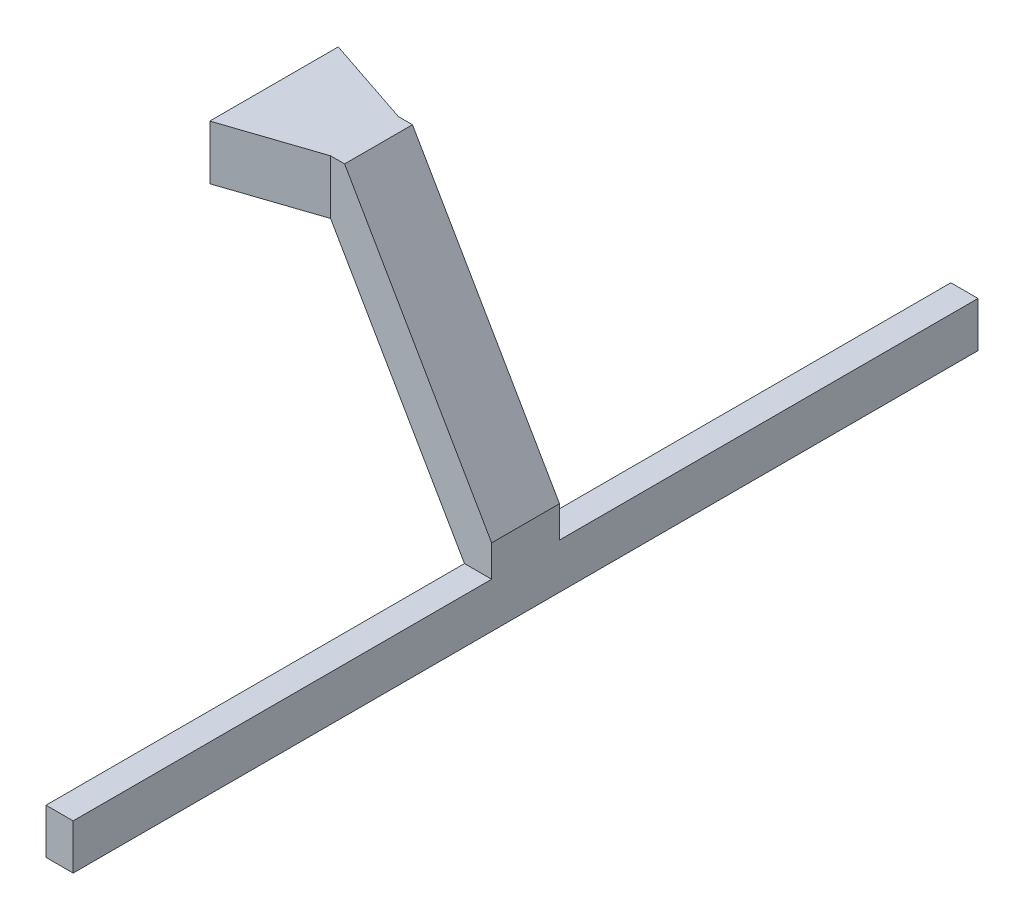
SolidWorks part; units mm, degrees
ref_plane "Plan de face" through (0, 0, 0) normal (0, 0, 1) x (1, 0, 0)
ref_plane "Plan de dessus" through (0, 0, 0) normal (0, 1, 0) x (1, 0, 0)
ref_plane "Plan de droite" through (0, 0, 0) normal (1, 0, 0) x (0, 0, -1)
sketch "Esquisse1" plane through (0, 0, 0) normal (0, 0, 1) x (1, 0, 0)
  line L0 (-29.9025, 15.2237) -> (-6.8025, 15.2237)
  line L1 (-6.8025, 15.2237) -> (25.6975, -41.0679)
  line L4 (19.6975, -58.0333) -> (19.6975, -48.0333)
  line L5 (19.6975, -48.0333) -> (-9.8958, 3.2237)
  line L6 (-9.8958, 3.2237) -> (-29.9025, 3.2237)
  line L7 (-29.9025, 3.2237) -> (-29.9025, 15.2237)
  line L8 (25.6975, -41.0679) -> (25.6975, -58.0333)
  line L9 (25.6975, -58.0333) -> (19.6975, -58.0333)
  dimension "D1" = 23.1
  dimension "D2" = 12
  dimension "D3" = 6
  dimension "D4" = 120
  dimension "D5" = 65
  dimension "D6" = 10
extrude "Boss.-Extru.1" add sketch "Esquisse1" along normal blind 15
sketch "Esquisse5" plane through (25.6975, 0, 0) normal (1, 0, 0) x (0, 0, -1)
  line L0 (-15, -58.0333) -> (0, -58.0333) construction
  line L1 (-107.5, -48.0333) -> (92.5, -48.0333)
  line L2 (-107.5, -48.0333) -> (-107.5, -58.0333)
  line L3 (-107.5, -58.0333) -> (92.5, -58.0333)
  line L4 (92.5, -48.0333) -> (92.5, -58.0333)
  line L6 (0, -58.0333) -> (0, -41.0679) construction
  line L7 (-15, -58.0333) -> (-15, -41.0679) construction
  dimension "D1" = 0
  dimension "D2" = 10
  dimension "D3" = 92.5
  dimension "D4" = 92.5
extrude "Boss.-Extru.4" add sketch "Esquisse5" against normal blind 6
sketch "Esquisse6" plane through (0, 15.2237, 0) normal (0, 1, 0) x (1, 0, 0)
  line L0 (-29.9025, -15) -> (-9.8958, -15)
  line L1 (-9.8958, -15) -> (-29.9025, -21.7026)
  line L2 (-29.9025, -21.7026) -> (-29.9025, -15)
extrude "Boss.-Extru.5" add sketch "Esquisse6" against normal blind 12
sketch "Esquisse7" plane through (0, 15.2237, 0) normal (0, 1, 0) x (1, 0, 0)
  line L0 (-29.9025, 0) -> (-9.8958, 0)
  line L1 (-9.8958, 0) -> (-29.9025, 6.6924)
  line L2 (-29.9025, 6.6924) -> (-29.9025, 0)
extrude "Boss.-Extru.6" add sketch "Esquisse7" against normal blind 12
